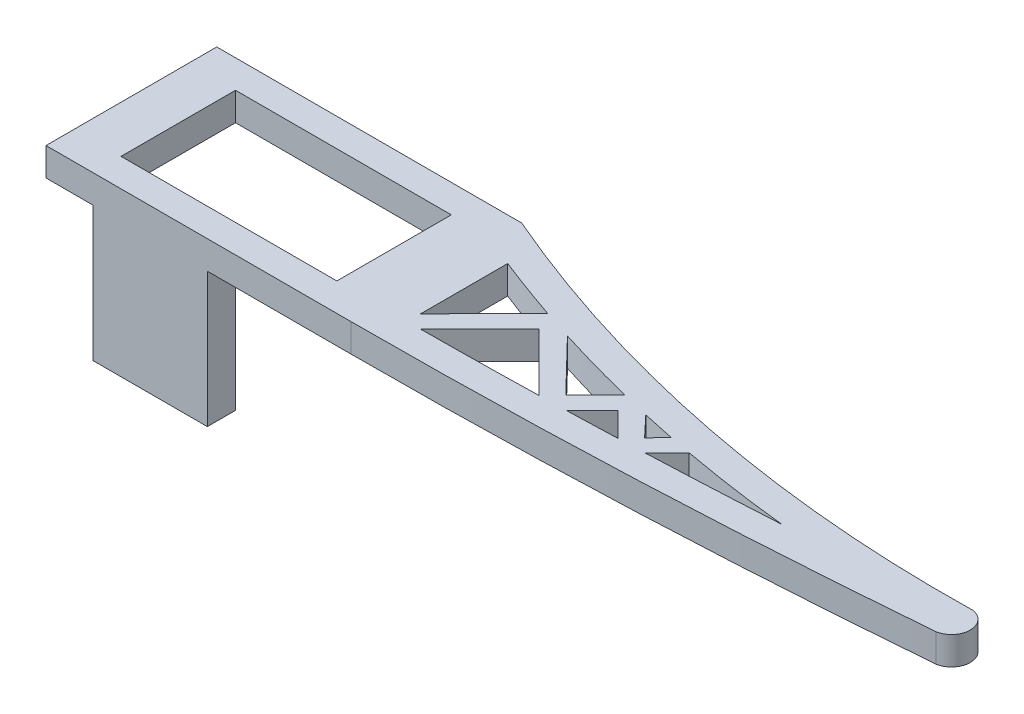
SolidWorks part; units mm, degrees
ref_plane "Front Plane" through (0, 0, 0) normal (0, 0, 1) x (1, 0, 0)
ref_plane "Top Plane" through (0, 0, 0) normal (0, 1, 0) x (1, 0, 0)
ref_plane "Right Plane" through (0, 0, 0) normal (1, 0, 0) x (0, 0, -1)
sketch "Sketch3" plane through (0, 0, 0) normal (0, 1, 0) x (1, 0, 0)
  line L1 (-11.25, 6.2) -> (11.75, 6.2)
  line L2 (-11.25, 6.2) -> (-11.25, -6)
  line L3 (-11.25, -6) -> (11.75, -6)
  line L4 (11.75, 6.2) -> (11.75, -6)
  line L5 (-16.25, 9.2) -> (16.25, 9.2)
  line L6 (-16.25, 9.2) -> (-16.25, -9)
  line L7 (-16.25, -9) -> (16.25, -9)
  line L13 (16.25, -9) -> (77.7339, -9) construction
  line L14 (77.7339, -9) -> (77.7339, 0.0031) construction
  line L15 (77.7339, -4.4984) -> (83.9654, -4.4984) construction
  line L16 (0, 0) -> (77.7339, 0.0031) construction
  arc A4 (76.0731, -6.4437) -> (76.0731, -2.5015) centre (75.7341, -4.4726) ccw
  arc A6 (16.25, -9) -> (76.0731, -6.4437) centre (16.25, 692.2678) ccw
  arc A10 (16.25, 9.2) -> (76.0731, -2.5015) centre (73.0415, 140.7708) ccw
  dimension "D6" = 2
  dimension "D1" = 12.2
  dimension "D2" = 23
  dimension "D3" = 32.5
  dimension "D4" = 18.2
  dimension "D5" = 3
extrude "Boss-Extrude1" add sketch "Sketch3" along normal blind 3
sketch "Sketch5" plane through (0, 3, 0) normal (0, 1, 0) x (1, 0, 0)
  line L1 (11.75, -6) -> (11.75, 6.2) construction
  line L2 (16.25, 9.2) -> (16.25, -9) construction
  line L3 (11.25, -9) -> (16.25, -9) construction
  line L4 (-16.25, -9) -> (16.25, -9) construction
  line L5 (11.75, 0.1) -> (11.75, -4.5) construction
  line L6 (19.25, -4.5) -> (19.3282, -4.5) construction
  line L8 (19.25, 4.714) -> (19.25, -4.5793)
  line L14 (20.6718, -5.986) -> (26.9906, 0.3328)
  line L15 (26.9906, 0.3328) -> (33.1196, -5.7962)
  line L16 (35.9529, -5.722) -> (38.6988, -2.9761)
  line L17 (38.6988, -2.9761) -> (41.2741, -5.5515)
  line L18 (44.1095, -5.444) -> (46.395, -3.0866)
  line L19 (19.25, -4.5793) -> (25.9777, 2.2429)
  line L20 (29.1124, 1.2172) -> (34.4991, -4.3473)
  line L21 (34.4991, -4.3473) -> (37.5887, -1.1731)
  line L22 (40.5625, -1.883) -> (42.6381, -4.087)
  line L23 (42.6381, -4.087) -> (44.0225, -2.6268)
  line L35 (19.25, 4.714) -> (19.25, -5.9936) construction
  arc A0 (16.25, 9.2) -> (76.0731, -2.5015) centre (73.0415, 140.7708) ccw construction
  arc A2 (35.9529, -5.722) -> (41.2741, -5.5515) centre (16.25, 692.2678) ccw
  arc A3 (44.1095, -5.444) -> (57.9535, -4.7535) centre (16.25, 692.2678) ccw
  arc A4 (20.6718, -5.986) -> (33.1196, -5.7962) centre (16.25, 692.2678) ccw
  arc A5 (19.25, 4.714) -> (25.9777, 2.2429) centre (73.0415, 140.7708) ccw
  arc A6 (19.25, 4.714) -> (76.1365, -5.5009) centre (73.0415, 140.7708) ccw construction
  arc A7 (40.5625, -1.883) -> (44.0225, -2.6268) centre (73.0415, 140.7708) ccw
  arc A8 (19.25, -5.9936) -> (75.8171, -3.4546) centre (16.25, 692.2678) ccw construction
  arc A9 (46.395, -3.0866) -> (57.9535, -4.7535) centre (73.0415, 140.7708) ccw
  arc A10 (29.1124, 1.2172) -> (37.5887, -1.1731) centre (73.0415, 140.7708) ccw
  arc A11 (16.25, -9) -> (76.0731, -6.4437) centre (16.25, 692.2678) ccw construction
extrude "Cut-Extrude1" cut sketch "Sketch5" against normal through all
sketch "Sketch6" plane through (0, 0, 0) normal (0, -1, 0) x (1, 0, 0)
  line L0 (-16.25, 9) -> (16.25, 9) construction
  line L1 (-11.25, 6) -> (0.95, 6)
  line L2 (-11.25, 6) -> (-11.25, 9)
  line L3 (-11.25, 9) -> (0.95, 9)
  line L4 (0.95, 6) -> (0.95, 9)
  dimension "D1" = 12.2
extrude "Boss-Extrude2" add sketch "Sketch6" along normal blind 14.35
